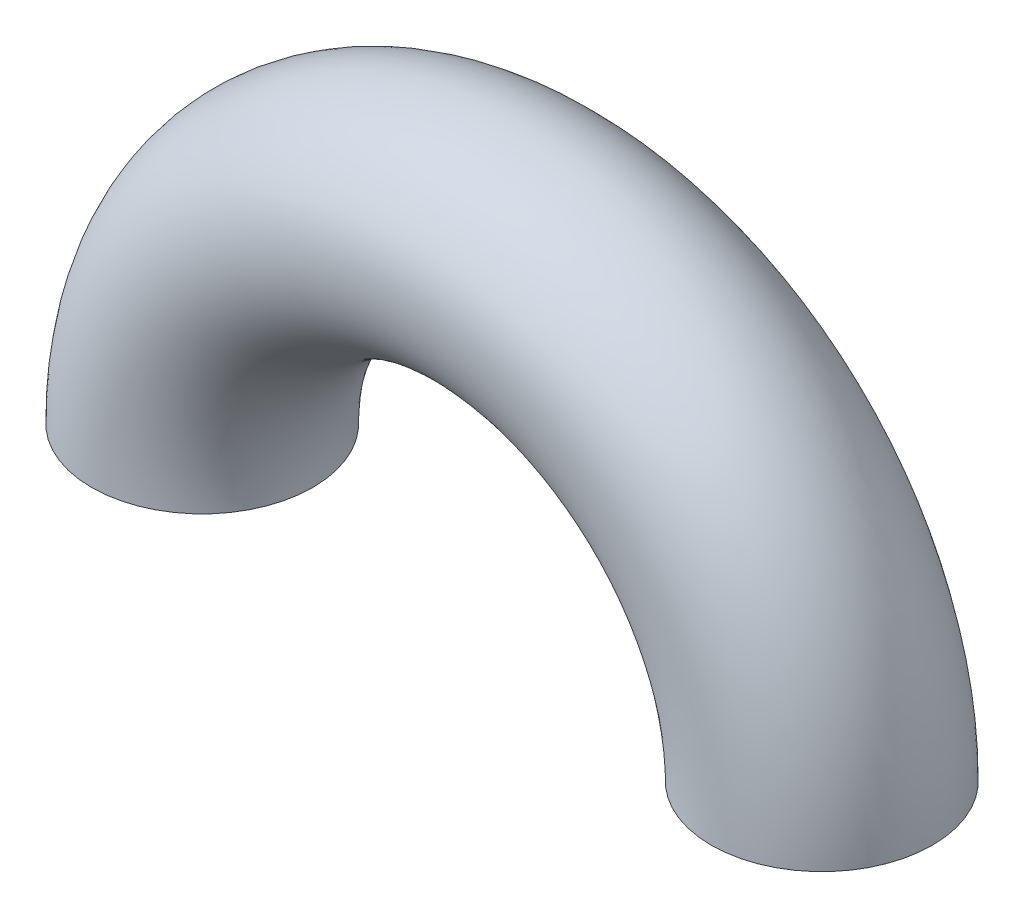
SolidWorks part; units mm, degrees
ref_plane "Front Plane" through (0, 0, 0) normal (0, 0, 1) x (1, 0, 0)
ref_plane "Top Plane" through (0, 0, 0) normal (0, 1, 0) x (1, 0, 0)
ref_plane "Right Plane" through (0, 0, 0) normal (1, 0, 0) x (0, 0, -1)
sketch "Sketch1" plane through (0, 0, 0) normal (0, 1, 0) x (1, 0, 0)
  line L0 (-70, 98) -> (-70, -89.04) construction
  circle A1 centre (0, 0) radius 25
  dimension "D2" = 50
  dimension "D1" = 70
revolve "Revolve-Thin1" add sketch "Sketch1" angle 180 about L0 wall 5
